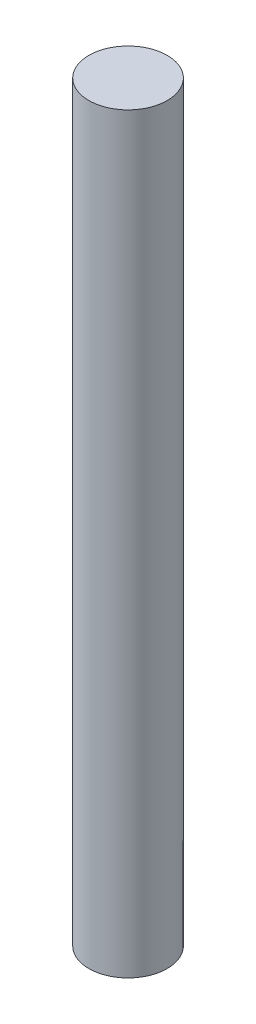
SolidWorks part; units mm, degrees
ref_plane "Front Plane" through (0, 0, 0) normal (0, 0, 1) x (1, 0, 0)
ref_plane "Top Plane" through (0, 0, 0) normal (0, 1, 0) x (1, 0, 0)
ref_plane "Right Plane" through (0, 0, 0) normal (1, 0, 0) x (0, 0, -1)
sketch "Sketch1" plane through (0, 0, 0) normal (0, 1, 0) x (1, 0, 0)
  circle A0 centre (0, 0) radius 1.5875
  dimension "D1" = 3.175
extrude "Boss-Extrude1" add sketch "Sketch1" along normal blind 30.48
